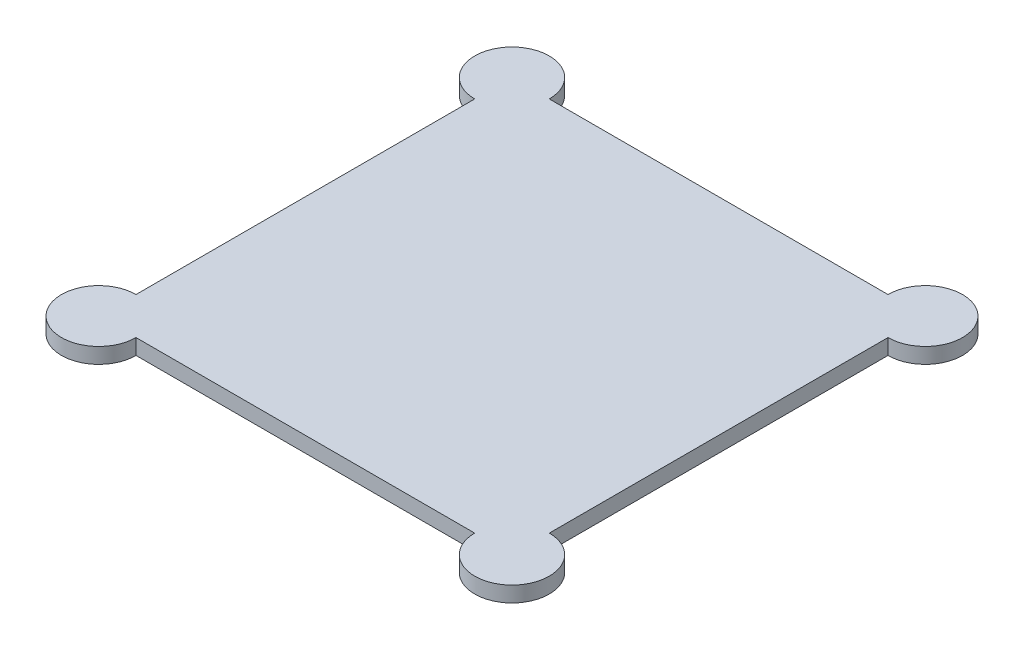
SolidWorks part; units mm, degrees
ref_plane "前视基准面" through (0, 0, 0) normal (0, 0, 1) x (1, 0, 0)
ref_plane "上视基准面" through (0, 0, 0) normal (0, 1, 0) x (1, 0, 0)
ref_plane "右视基准面" through (0, 0, 0) normal (1, 0, 0) x (0, 0, -1)
other "Configuration Table"
sketch "草图1" plane through (0, 0, 0) normal (0, 1, 0) x (1, 0, 0)
  line L1 (-133, 133) -> (133, 133)
  line L2 (-133, 133) -> (-133, -133)
  line L3 (-133, -133) -> (133, -133)
  line L4 (133, 133) -> (133, -133)
  line L5 (-133, 133) -> (133, -133) construction
  line L6 (-133, -133) -> (133, 133) construction
  circle A0 centre (-133, 133) radius 24
  circle A1 centre (133, 133) radius 24
  circle A2 centre (133, -133) radius 24
  circle A3 centre (-133, -133) radius 24
  point P0 (0, 0)
  point P11 (0, 0)
  dimension "D3" = 48
  dimension "D1" = 266
  dimension "D2" = 266
extrude "凸台-拉伸1" add sketch "草图1" along normal blind 10 contours L1 A0 L2 | L2 A0 L1 | A3 L3 A2 L4 A1 L1 A0 L2 | L1 A1 L4 | L4 A1 L1 | L4 A2 L3 | L3 A2 L4 | L3 A3 L2 | L2 A3 L3
